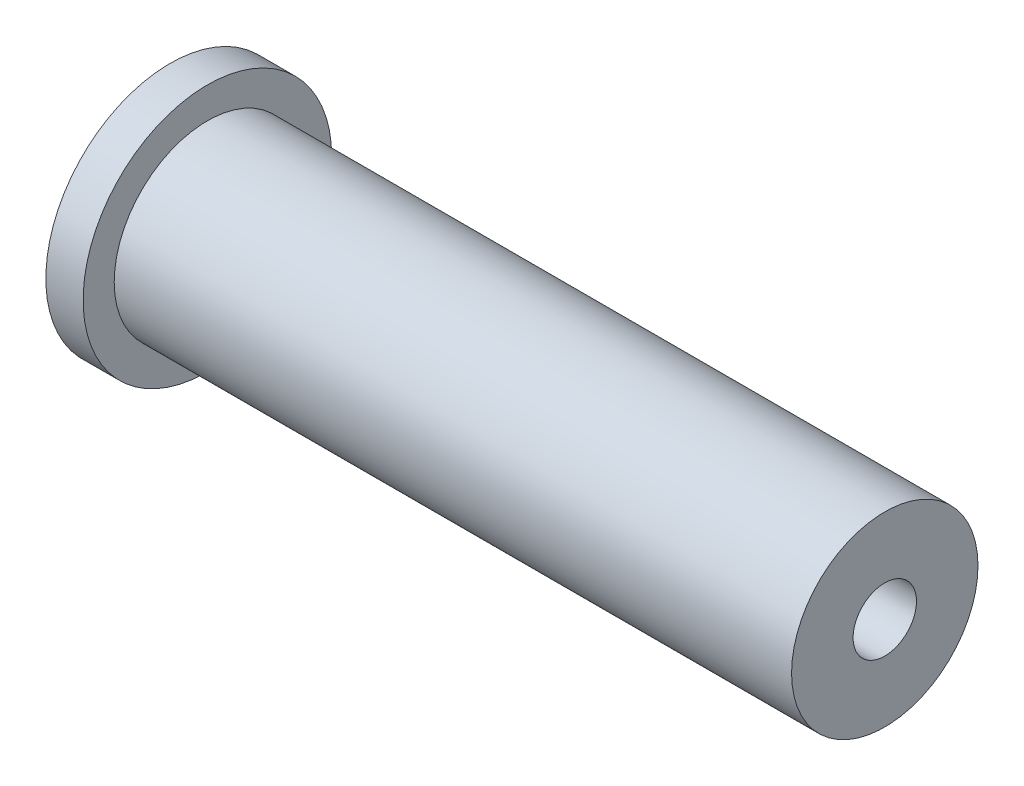
SolidWorks part; units mm, degrees
material "AISI 1020"
ref_plane "Front Plane" through (0, 0, 0) normal (0, 0, 1) x (1, 0, 0)
ref_plane "Top Plane" through (0, 0, 0) normal (0, 1, 0) x (1, 0, 0)
ref_plane "Right Plane" through (0, 0, 0) normal (1, 0, 0) x (0, 0, -1)
sketch "Sketch1" plane through (0, 0, 0) normal (0, 0, 1) x (1, 0, 0)
  line L0 (0, 0) -> (0, 10)
  line L1 (0, 10) -> (3, 10)
  line L2 (3, 10) -> (3, 7.5)
  line L3 (3, 7.5) -> (57.5, 7.5)
  line L4 (57.5, 7.5) -> (57.5, 0)
  line L5 (57.5, 0) -> (0, 0)
  line L6 (0, 0) -> (-5.4432, 0) construction
  dimension "D1" = 54.5
  dimension "D2" = 3
  dimension "D3" = 15
  dimension "D4" = 20
revolve "Revolve1" add sketch "Sketch1" angle 360 about L6
sketch "Sketch2" plane through (57.5, 0, 0) normal (1, 0, 0) x (0, 0, -1)
  circle A0 centre (0, 0) radius 2.55
  dimension "D1" = 5.1
extrude "Cut-Extrude1" cut sketch "Sketch2" against normal blind 10
cosmetic thread "Cosmetic Thread1" parameters "D1"=8, "D2"=6
